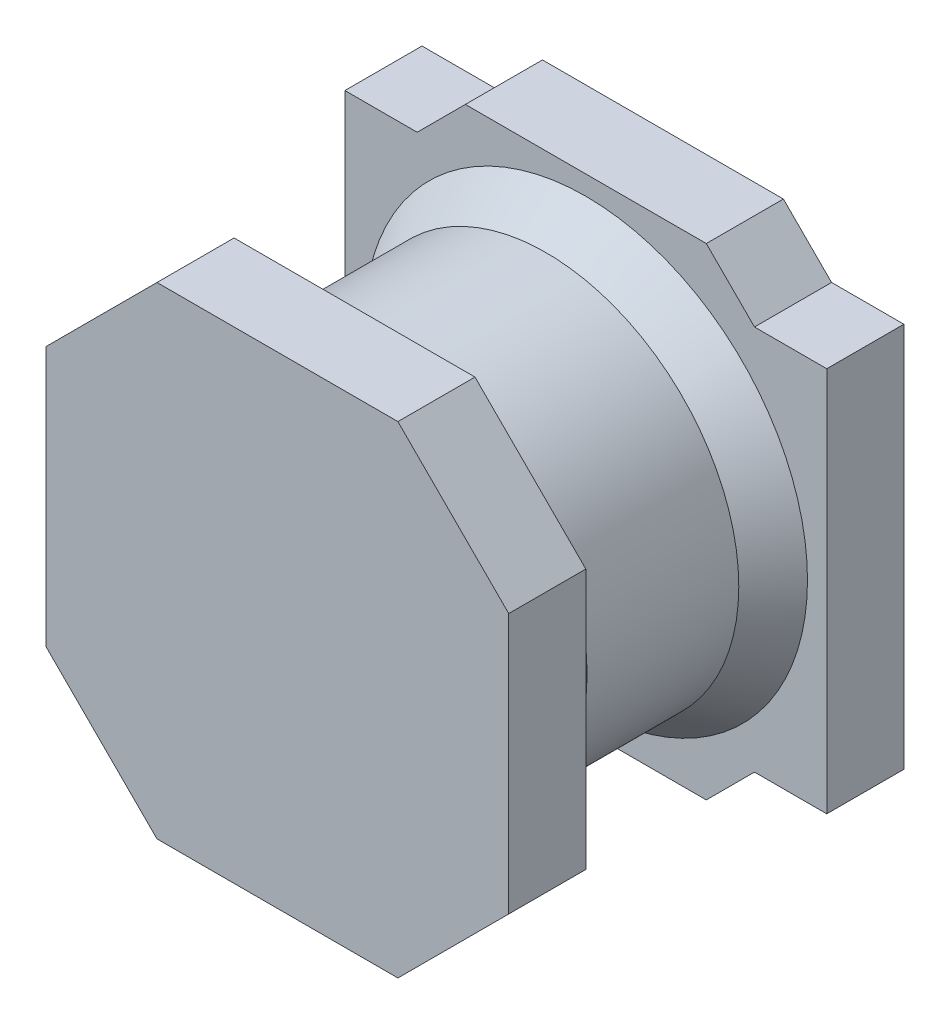
SolidWorks part; units mm, degrees
ref_plane "Front Plane" through (0, 0, 0) normal (0, 0, 1) x (1, 0, 0)
ref_plane "Top Plane" through (0, 0, 0) normal (0, 1, 0) x (1, 0, 0)
ref_plane "Right Plane" through (0, 0, 0) normal (1, 0, 0) x (0, 0, -1)
sketch "Sketch1" plane through (0, 0, 0) normal (0, 0, 1) x (1, 0, 0)
  line L0 (0, 0) -> (0, 2.5) construction
  line L1 (0, 0) -> (2.5, 0) construction
  line L2 (-1.25, 2.5) -> (1.25, 2.5)
  line L3 (1.25, 2.5) -> (1.75, 2)
  line L4 (1.75, 2) -> (2.5, 2)
  line L5 (2.5, 2) -> (2.5, -2)
  line L6 (-1.75, 2) -> (-2.5, 2)
  line L7 (-2.5, 2) -> (-2.5, -2)
  line L8 (-1.25, 2.5) -> (-1.75, 2)
  line L9 (1.75, -2) -> (2.5, -2)
  line L10 (1.25, -2.5) -> (1.75, -2)
  line L11 (-1.25, -2.5) -> (1.25, -2.5)
  line L12 (-1.25, -2.5) -> (-1.75, -2)
  line L13 (-1.75, -2) -> (-2.5, -2)
  point P17 (-2.5, 0)
  dimension "D1" = 5
  dimension "D2" = 5
  dimension "D3" = 45
  dimension "D4" = 4
  dimension "D5" = 2.5
extrude "Boss-Extrude1" add sketch "Sketch1" along normal blind 0.8
sketch "Sketch2" plane through (0, 0, 0) normal (0, 1, 0) x (1, 0, 0)
  line L0 (0, -0.8) -> (0, -3.2)
  line L1 (1.25, -0.8) -> (-1.25, -0.8) construction
  line L2 (0, -0.8) -> (2.3, -0.8)
  line L3 (2.5, -0.8) -> (1.75, -0.8) construction
  line L4 (2.3, -0.8) -> (2, -1.2129)
  line L5 (2, -1.2129) -> (2, -2.7871)
  line L6 (2, -2.7871) -> (2.3, -3.2)
  line L7 (2.3, -3.2) -> (0, -3.2)
  line L8 (2.3, -3.2) -> (2.3, -0.8) construction
  point P5 (2, -2.8036)
  dimension "D1" = 2.3
  dimension "D2" = 0.3
  dimension "D3" = 2.4
  dimension "D4" = 54
revolve "Revolve1" add sketch "Sketch2" angle 360 about L0
sketch "Sketch3" plane through (0, 0, 3.2) normal (0, 0, 1) x (1, 0, 0)
  line L0 (1.25, 2.5) -> (-1.25, 2.5) construction
  line L1 (-1.25, 2.5) -> (1.25, 2.5)
  line L2 (1.25, 2.5) -> (2.4, 1.35)
  line L3 (2.4, 1.35) -> (2.4, -1.35)
  line L4 (2.4, 0) -> (0, 0) construction
  line L5 (0, 0) -> (0, 2.5) construction
  line L6 (1.75, 2) -> (1.25, 2.5) construction
  line L7 (-2.4, 1.35) -> (-2.4, -1.35)
  line L8 (-1.25, 2.5) -> (-2.4, 1.35)
  line L9 (1.25, -2.5) -> (2.4, -1.35)
  line L10 (-1.25, -2.5) -> (1.25, -2.5)
  line L11 (-1.25, -2.5) -> (-2.4, -1.35)
  point P0 (2.244, 1.3709)
  point P20 (-2.4, 0)
  dimension "D1" = 2.4
extrude "Boss-Extrude2" add sketch "Sketch3" along normal blind 0.8
